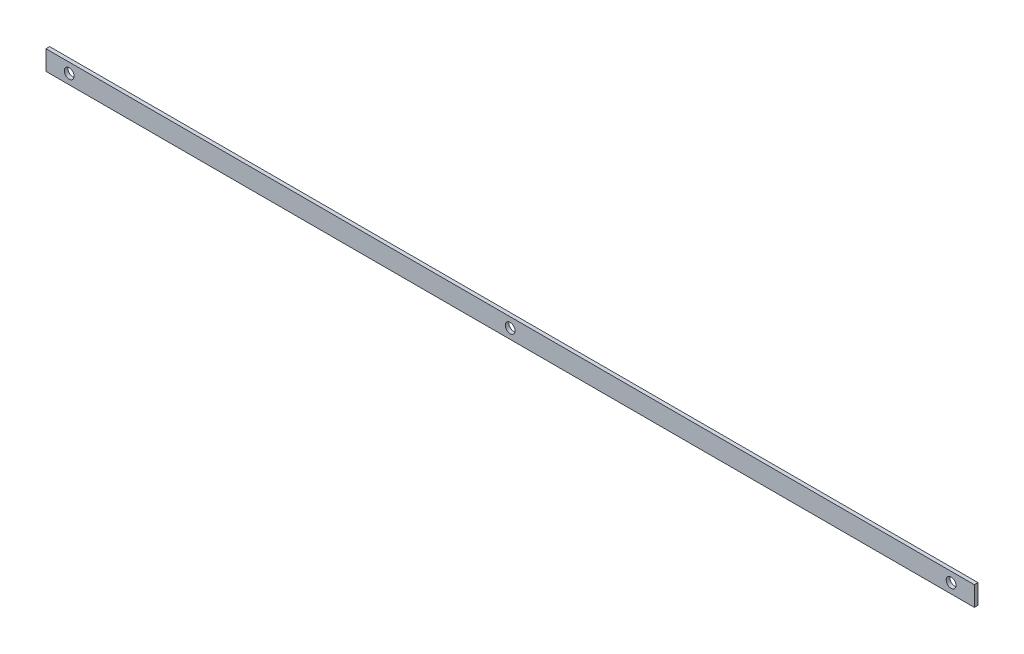
SolidWorks part; units mm, degrees
ref_plane "Alzado" through (0, 0, 0) normal (0, 0, 1) x (1, 0, 0)
ref_plane "Planta" through (0, 0, 0) normal (0, 1, 0) x (1, 0, 0)
ref_plane "Vista lateral" through (0, 0, 0) normal (1, 0, 0) x (0, 0, -1)
sketch "Croquis1" plane through (0, 0, 0) normal (0, 0, 1) x (1, 0, 0)
  line L1 (0, 0) -> (2400, 0)
  line L2 (0, 0) -> (0, -50.8)
  line L3 (0, -50.8) -> (2400, -50.8)
  line L4 (2400, 0) -> (2400, -50.8)
  dimension "D1" = 50.8
  dimension "D2" = 2400
extrude "Saliente-Extruir1" add sketch "Croquis1" along normal blind 9.525
sketch "Croquis2" plane through (0, 0, 9.525) normal (0, 0, 1) x (1, 0, 0)
  line L0 (0, -25.4) -> (60, -25.4) construction
  line L1 (0, 0) -> (0, -50.8) construction
  line L2 (1200, 0) -> (1200, -50.8) construction
  line L3 (2400, 0) -> (0, 0) construction
  line L4 (0, -50.8) -> (2400, -50.8) construction
  line L5 (2400, -25.4) -> (2340, -25.4) construction
  circle A0 centre (60, -25.4) radius 12.7
  circle A1 centre (2340, -25.4) radius 12.7
  circle A2 centre (1200, -25.4) radius 12.7
  dimension "D2" = 25.4
  dimension "D3" = 25.4
  dimension "D1" = 60
extrude "Cortar-Extruir1" cut sketch "Croquis2" against normal blind 20
